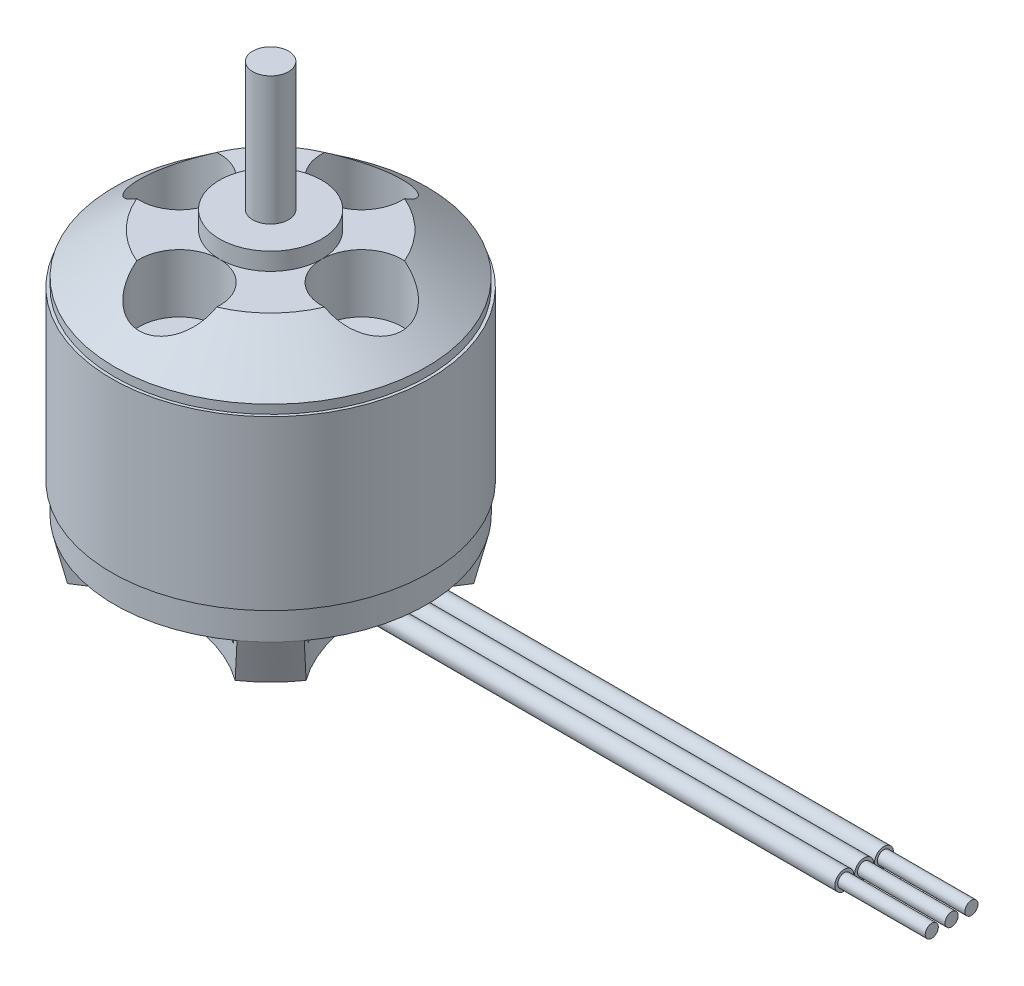
SolidWorks part; units mm, degrees
material "Plain Carbon Steel"
ref_plane "Front" through (0, 0, 0) normal (0, 0, 1) x (1, 0, 0)
ref_plane "Top" through (0, 0, 0) normal (0, 1, 0) x (1, 0, 0)
ref_plane "Right" through (0, 0, 0) normal (1, 0, 0) x (0, 0, -1)
sketch "Sketch1" plane through (0, 0, 0) normal (0, 0, 1) x (1, 0, 0)
  line L0 (0, 11.176) -> (1.5558, 11.176)
  line L1 (0, -50) -> (0, 50) construction
  line L2 (1.5558, 11.176) -> (1.5558, 0)
  line L3 (50, 0) -> (-50, 0) construction
  line L4 (1.5558, 0) -> (4.445, 0)
  line L5 (4.445, 0) -> (4.445, -1.524)
  line L6 (4.445, -1.524) -> (8.89, -1.524)
  line L7 (8.89, -1.524) -> (13.589, -5.08)
  line L8 (13.589, -5.08) -> (13.589, -5.842)
  line L9 (13.589, -5.842) -> (13.843, -5.842)
  line L10 (13.843, -5.842) -> (13.843, -20.4724)
  line L11 (13.589, -20.4724) -> (13.589, -23.0124)
  line L12 (13.589, -23.0124) -> (12.7, -26.67)
  line L13 (12.7, -26.67) -> (3.81, -26.67)
  line L14 (3.81, -26.67) -> (3.81, -26.924)
  line L15 (3.81, -26.924) -> (1.5558, -26.924)
  line L16 (1.5558, -26.924) -> (1.5558, -28.956)
  line L17 (1.5558, -28.956) -> (0, -28.956)
  line L18 (0, -28.956) -> (0, 11.176)
  line L19 (13.589, -20.4724) -> (13.843, -20.4724)
  dimension "D1" = 13.843
  dimension "D2" = 1.5557
  dimension "D3" = 11.176
  dimension "D4" = 4.445
  dimension "D5" = 1.524
  dimension "D6" = 8.89
  dimension "D7" = 4.318
  dimension "D8" = 0.762
  dimension "D9" = 0.254
  dimension "D10" = 14.6304
  dimension "D11" = 2.54
  dimension "D12" = 25.146
  dimension "D13" = 12.7
  dimension "D14" = 3.81
  dimension "D15" = 0.254
  dimension "D16" = 40.132
revolve "Revolve1" add sketch "Sketch1" angle 360 about L18
sketch "Sketch2" plane through (0, -1.524, 0) normal (0, 1, 0) x (1, 0, 0)
  circle A0 centre (0, 7.9375) radius 3.4925
  circle A1 centre (7.9375, 0) radius 3.4925
  circle A2 centre (0, -7.9375) radius 3.4925
  circle A3 centre (-7.9375, 0) radius 3.4925
  circle A5 centre (0, 0) radius 4.445 construction
  circle A7 centre (0, 0) radius 4.445 construction
  dimension "D2" = 6.985
extrude "Cut-Extrude1" cut sketch "Sketch2" against normal blind 5.08
sketch "Sketch3" plane through (0, -26.67, 0) normal (0, -1, 0) x (1, 0, 0)
  line L1 (-7.3025, 10.3905) -> (7.3025, 10.3905) construction
  circle A0 centre (0, 20.4866) radius 12.4602
  circle A1 centre (-20.4866, 0) radius 12.4602
  circle A2 centre (0, -20.4866) radius 12.4602
  circle A3 centre (20.4866, 0) radius 12.4602
  circle A4 centre (0, 0) radius 8.0264 construction
  circle A5 centre (0, 0) radius 12.7 construction
  dimension "D1" = 16.0528
  dimension "D2" = 14.605
extrude "Cut-Extrude2" cut sketch "Sketch3" against normal offset from surface (3.6576 mm away) 2.54 up to face at (0, -20.4724, -13.843)
sketch "Sketch4" plane through (0, -23.0124, 0) normal (0, -1, 0) x (1, 0, 0)
  circle A0 centre (0, 0) radius 12.1158
  arc A2 (8.0324, 10.9609) -> (-8.0324, 10.9609) centre (0, 0) ccw construction
  dimension "D1" = 1.4732
extrude "Cut-Extrude3" cut sketch "Sketch4" against normal blind 2.54 and the other way blind 1.27
sketch "Sketch10" plane through (0, 0, 0) normal (1, 0, 0) x (0, 0, -1)
  line L1 (-12.1158, -20.4724) -> (12.1158, -20.4724) construction
  line L2 (-1.7272, -21.2979) -> (0, -21.2979) construction
  line L3 (0, -21.2979) -> (1.7272, -21.2979) construction
  circle A0 centre (0, -21.2979) radius 0.8255
  circle A1 centre (-1.7272, -21.2979) radius 0.8255
  circle A2 centre (1.7272, -21.2979) radius 0.8255
  dimension "D1" = 1.651
  dimension "D2" = 1.7272
sketch "Sketch12" plane through (0, 0, 0) normal (0, 0, 1) x (1, 0, 0)
  line L0 (0, -21.2979) -> (3.81, -21.2979)
  line L1 (0, -22.1234) -> (0, -20.4724) construction
  line L2 (9.5697, -23.8815) -> (51.689, -23.8815)
  line L3 (-13.843, -20.4724) -> (13.843, -20.4724) construction
  line L4 (-13.843, -20.4724) -> (13.589, -20.4724) construction
  line L5 (13.589, -23.0124) -> (13.589, -20.4724) construction
  arc A0 (3.81, -21.2979) -> (6.6898, -22.5897) centre (3.81, -25.1539) cw
  arc A1 (6.6898, -22.5897) -> (9.5697, -23.8815) centre (9.5697, -20.0255) ccw
  dimension "D1" = 2.5836
  dimension "D2" = 38.1
  dimension "D3" = 3.81
sweep "Sweep1" add profiles "Sketch10" path "Sketch12"
sketch "Sketch13" plane through (51.689, 0, 0) normal (1, 0, 0) x (0, 0, -1)
  circle A0 centre (1.7272, -23.8815) radius 0.8255 construction
  circle A1 centre (0, -23.8815) radius 0.8255 construction
  circle A2 centre (-1.7272, -23.8815) radius 0.8255 construction
  circle A3 centre (1.7272, -23.8815) radius 0.8255 construction
  circle A4 centre (0, -23.8815) radius 0.8255 construction
  circle A5 centre (-1.7272, -23.8815) radius 0.8255 construction
  circle A6 centre (1.7272, -23.8815) radius 0.5715
  circle A7 centre (0, -23.8815) radius 0.5715
  circle A8 centre (-1.7272, -23.8815) radius 0.5715
  dimension "D1" = 0.254
extrude "Boss-Extrude1" add sketch "Sketch13" along normal blind 7.62
